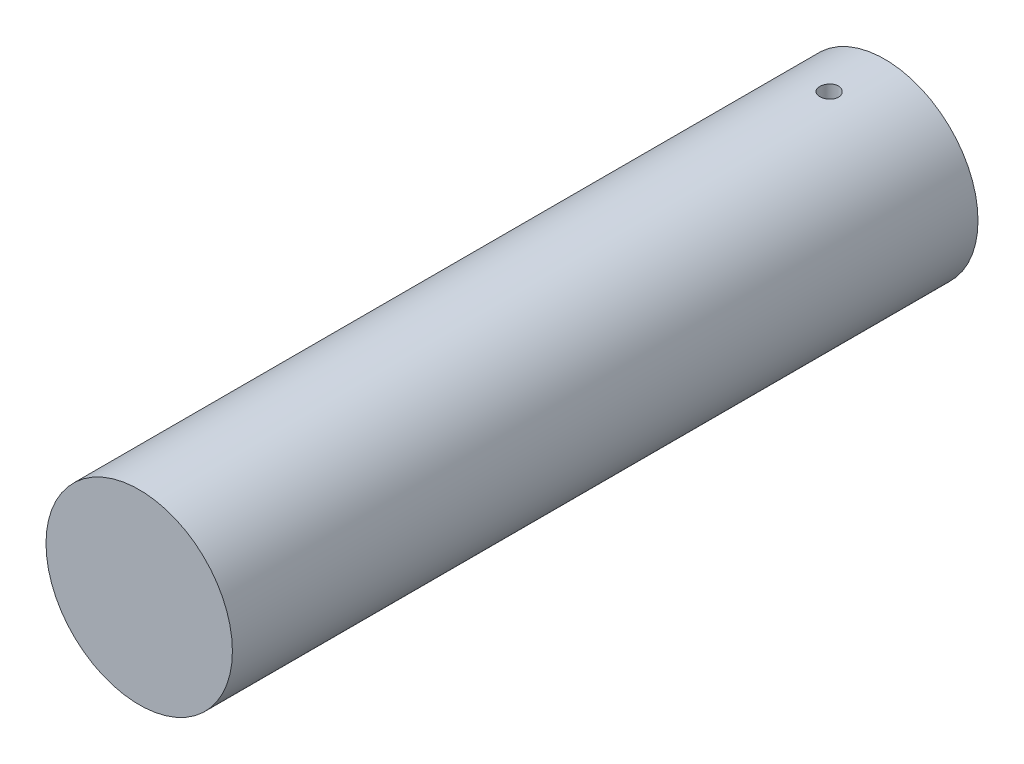
SolidWorks part; units mm, degrees
material "Lega 1060"
ref_plane "Piano frontale" through (0, 0, 0) normal (0, 0, 1) x (1, 0, 0)
ref_plane "Piano superiore" through (0, 0, 0) normal (0, 1, 0) x (1, 0, 0)
ref_plane "Piano destro" through (0, 0, 0) normal (1, 0, 0) x (0, 0, -1)
sketch "Schizzo1" plane through (0, 0, 0) normal (0, 0, 1) x (1, 0, 0)
  circle A0 centre (0, 0) radius 50
  dimension "D1" = 100
extrude "Estrusione-Estrusione1" add sketch "Schizzo1" along normal blind 400
sketch "Schizzo2" plane through (0, 0, 0) normal (0, 1, 0) x (1, 0, 0)
  circle A0 centre (0, -29.8952) radius 5
  dimension "D1" = 10
extrude "Taglio-Estrusione1" cut sketch "Schizzo2" against normal through all both and the other way through all
